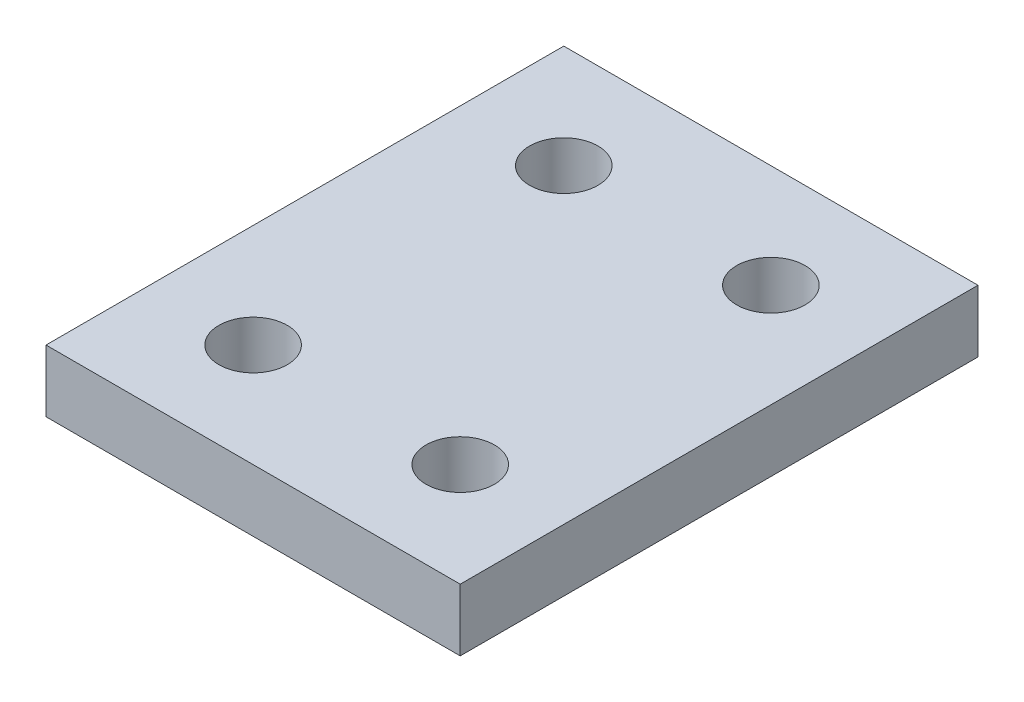
SolidWorks part; units mm, degrees
material "Thornel Mat VMA"
ref_plane "前视基准面" through (0, 0, 0) normal (0, 0, 1) x (1, 0, 0)
ref_plane "上视基准面" through (0, 0, 0) normal (0, 1, 0) x (1, 0, 0)
ref_plane "右视基准面" through (0, 0, 0) normal (1, 0, 0) x (0, 0, -1)
sketch "草图1" plane through (0, 0, 0) normal (0, 1, 0) x (1, 0, 0)
  line L1 (-10, 12.5) -> (10, 12.5)
  line L2 (-10, 12.5) -> (-10, -12.5)
  line L3 (-10, -12.5) -> (10, -12.5)
  line L4 (10, 12.5) -> (10, -12.5)
  line L5 (-10, 12.5) -> (10, -12.5) construction
  line L6 (-10, -12.5) -> (10, 12.5) construction
  point P0 (0, 0)
  dimension "D1" = 20
  dimension "D2" = 25
extrude "凸台-拉伸1" add sketch "草图1" along normal blind 3
sketch "草图2" plane through (0, 3, 0) normal (0, 1, 0) x (1, 0, 0)
  line L0 (0, 2.5) -> (-10, 12.5)
  line L1 (-10, 12.5) -> (0, 12.5)
  line L2 (-10, 12.5) -> (-10, 2.5)
  line L3 (-10, 2.5) -> (0, 2.5)
  line L4 (0, 12.5) -> (0, 2.5)
  line L5 (10, 12.5) -> (0, 12.5)
  line L6 (10, 12.5) -> (10, 2.5)
  line L7 (10, 2.5) -> (0, 2.5)
  line L8 (0, 12.5) -> (0, 2.5)
  line L9 (-10, -12.5) -> (0, -12.5)
  line L10 (-10, -12.5) -> (-10, -2.5)
  line L11 (-10, -2.5) -> (0, -2.5)
  line L12 (0, -12.5) -> (0, -2.5)
  line L13 (10, -12.5) -> (0, -12.5)
  line L14 (10, -12.5) -> (10, -2.5)
  line L15 (10, -2.5) -> (0, -2.5)
  line L16 (0, -12.5) -> (0, -2.5)
  line L17 (0, 2.5) -> (10, 12.5)
  line L18 (0, -2.5) -> (10, -12.5)
  line L19 (0, -2.5) -> (-10, -12.5)
  dimension "D1" = 10
  dimension "D2" = 10
  dimension "D3" = 10
  dimension "D4" = 10
  dimension "D5" = 10
  dimension "D6" = 10
  dimension "D7" = 10
  dimension "D8" = 10
sketch "草图3" plane through (0, 3, 0) normal (0, 1, 0) x (1, 0, 0)
  line L0 (0, 2.5) -> (-10, 12.5) construction
  line L1 (0, 2.5) -> (10, 12.5) construction
  line L2 (0, -2.5) -> (-10, -12.5) construction
  line L3 (0, -2.5) -> (10, -12.5) construction
  point P0 (-5, 7.5)
  point P4 (5, 7.5)
  point P8 (-5, -7.5)
  point P12 (5, -7.5)
hole_wizard "孔1" positions "草图3" profile "草图4" legacy end condition through all
sketch "草图4" plane through (-5, 3, -7.5) normal (1, 0, 0) x (0, 0, 1)
  line L0 (0, 0) -> (0, 3)
  line L1 (0, 3) -> (1.65, 3)
  line L2 (1.65, 3) -> (1.65, 0)
  line L3 (1.65, 0) -> (0, 0)
  line L4 (0, 110) -> (0, -10) construction
  dimension "直径" = 3.3
  dimension "深度" = 3
